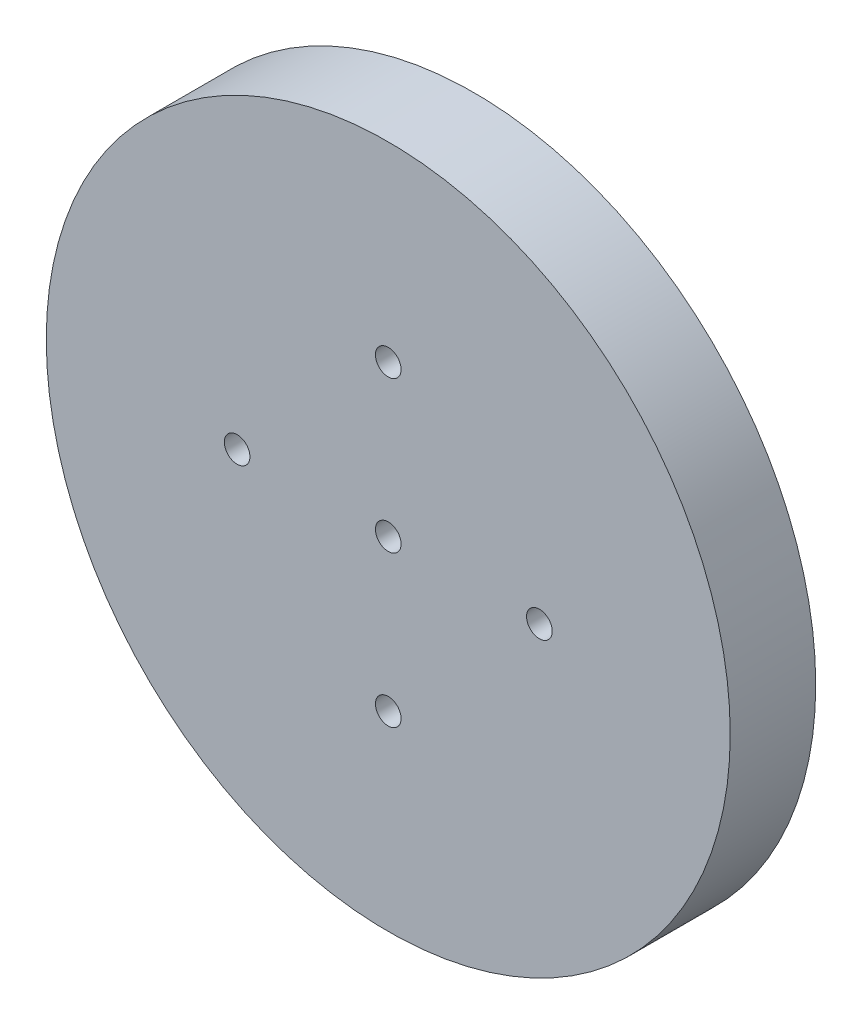
SolidWorks part; units mm, degrees
ref_plane "前视基准面" through (0, 0, 0) normal (0, 0, 1) x (1, 0, 0)
ref_plane "上视基准面" through (0, 0, 0) normal (0, 1, 0) x (1, 0, 0)
ref_plane "右视基准面" through (0, 0, 0) normal (1, 0, 0) x (0, 0, -1)
sketch "草图1" plane through (0, 0, 0) normal (0, 0, 1) x (1, 0, 0)
  circle A0 centre (0, 0) radius 40
  dimension "D1" = 80
extrude "凸台-拉伸1" add sketch "草图1" along normal blind 10
sketch "草图2" plane through (0, 0, 0) normal (0, 0, -1) x (-1, 0, 0)
  circle A0 centre (0, 0) radius 38.5
  dimension "D1" = 77
extrude "切除-拉伸1" cut sketch "草图2" against normal blind 7
sketch "草图4" plane through (0, 0, 10) normal (0, 0, 1) x (1, 0, 0)
  line L0 (-60.9278, 0) -> (72.5662, 0) construction
  line L1 (0, 46.9988) -> (0, -55.6743) construction
  line L2 (-17.6777, 0) -> (0, -17.6777)
  line L3 (0, 17.6777) -> (17.6777, 0)
  line L4 (0, -17.6777) -> (17.6777, 0)
  line L5 (-17.6777, 0) -> (0, 17.6777)
  circle A0 centre (0, 17.6777) radius 1.5
  circle A1 centre (17.6777, 0) radius 1.5
  circle A2 centre (0, -17.6777) radius 1.5
  circle A3 centre (-17.6777, 0) radius 1.5
  circle A4 centre (0, 0) radius 1.5
  dimension "D1" = 3
  dimension "D2" = 25
  dimension "D3" = 3
  dimension "D4" = 25
  dimension "D5" = 90
extrude "切除-拉伸2" cut sketch "草图4" against normal through all contours A2 | A1 | A0 | A3 | A4
